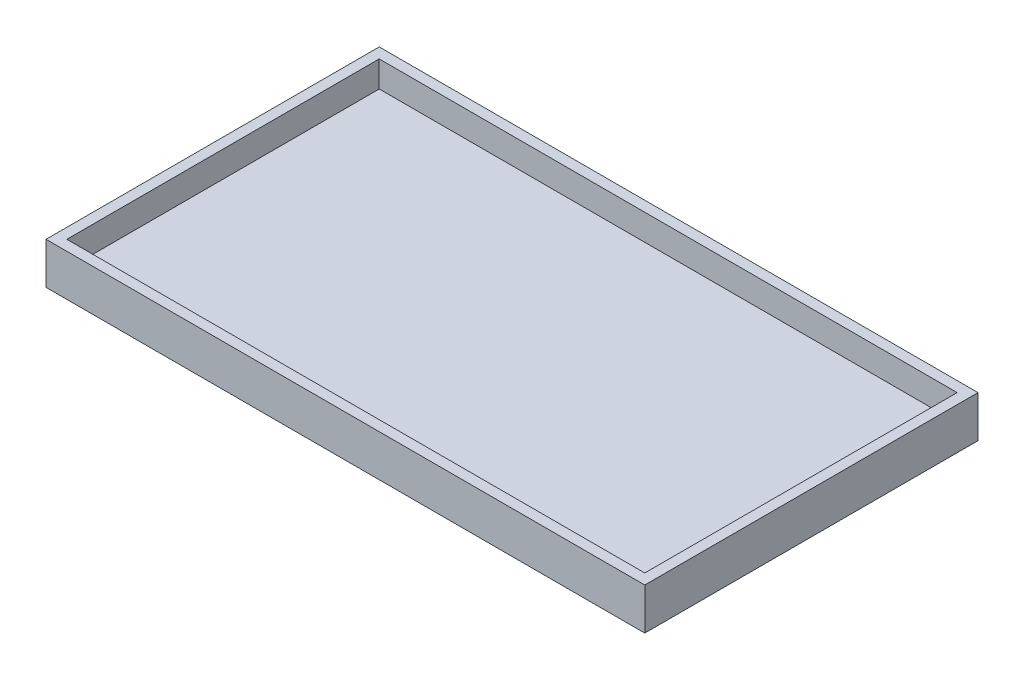
SolidWorks part; units mm, degrees
material "ABS"
ref_plane "Front Plane" through (0, 0, 0) normal (0, 0, 1) x (1, 0, 0)
ref_plane "Top Plane" through (0, 0, 0) normal (0, 1, 0) x (1, 0, 0)
ref_plane "Right Plane" through (0, 0, 0) normal (1, 0, 0) x (0, 0, -1)
sketch "Sketch1" plane through (0, 0, 0) normal (0, 1, 0) x (1, 0, 0)
  line L0 (-55, 0) -> (55, 0) construction
  line L1 (-57.5, 32) -> (57.5, 32)
  line L2 (-57.5, 32) -> (-57.5, -32)
  line L3 (-57.5, -32) -> (57.5, -32)
  line L4 (57.5, 32) -> (57.5, -32)
  line L5 (0, -55) -> (0, 55) construction
  dimension "D1" = 115
  dimension "D2" = 64
  dimension "D3" = 32
  dimension "D4" = 57.5
extrude "Boss-Extrude1" add sketch "Sketch1" along normal blind 3
sketch "Sketch2" plane through (0, 3, 0) normal (0, 1, 0) x (1, 0, 0)
  line L0 (57.5, 32) -> (-57.5, 32) construction
  line L1 (-55.5, -30) -> (55.5, -30)
  line L2 (-55.5, -30) -> (-55.5, 30)
  line L3 (-55.5, 30) -> (55.5, 30)
  line L4 (55.5, -30) -> (55.5, 30)
  line L5 (-55.5, -30) -> (55.5, 30) construction
  line L6 (-55.5, 30) -> (55.5, -30) construction
  line L7 (-57.5, 32) -> (-57.5, -32) construction
  line L9 (-57.5, -32) -> (57.5, -32)
  line L10 (-57.5, -32) -> (-57.5, 32)
  line L11 (-57.5, 32) -> (57.5, 32)
  line L12 (57.5, -32) -> (57.5, 32)
  line L13 (-57.5, -32) -> (57.5, 32) construction
  line L14 (-57.5, 32) -> (57.5, -32) construction
  point P0 (0, 0)
  point P10 (0, 0)
  dimension "D1" = 2
  dimension "D2" = 2
extrude "Boss-Extrude3" add sketch "Sketch2" along normal blind 5
